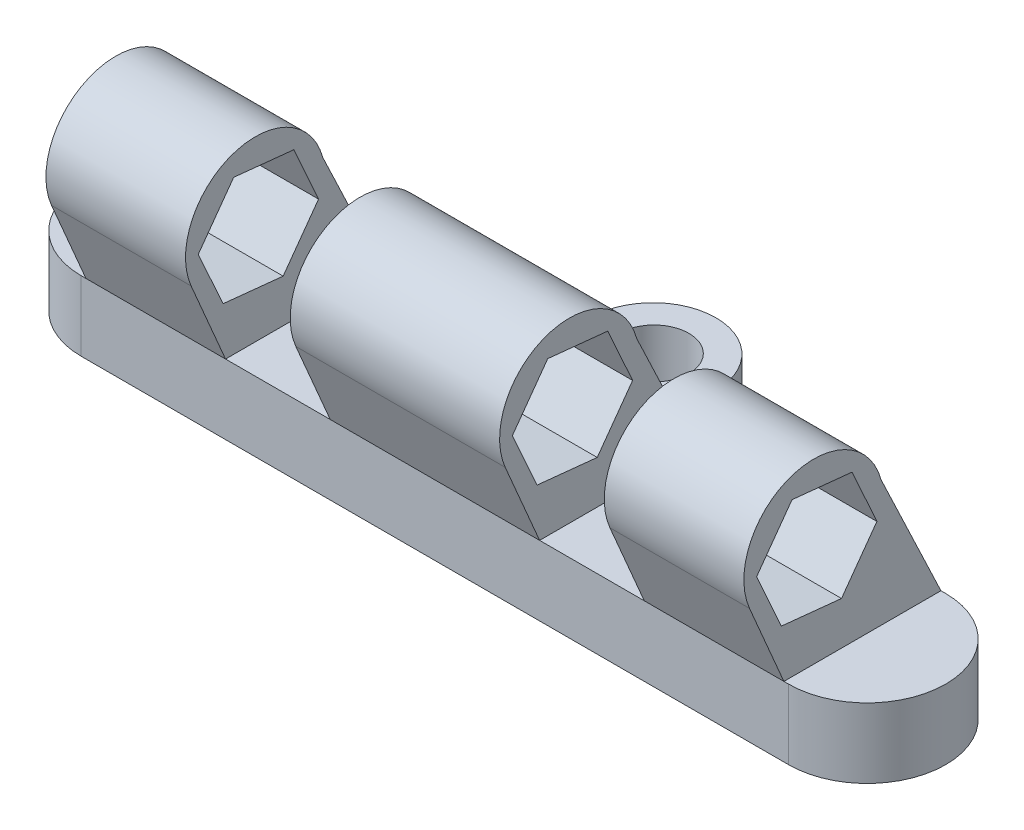
SolidWorks part; units mm, degrees
ref_plane "前视基准面" through (0, 0, 0) normal (0, 0, 1) x (1, 0, 0)
ref_plane "上视基准面" through (0, 0, 0) normal (0, 1, 0) x (1, 0, 0)
ref_plane "右视基准面" through (0, 0, 0) normal (1, 0, 0) x (0, 0, -1)
other "Configuration Table"
sketch "草图2" plane through (0, 0, 0) normal (0, 1, 0) x (1, 0, 0)
  line L1 (-10.1361, 2.25) -> (-1.8018, 2.25)
  line L2 (-10.1361, -2.25) -> (10.1361, -2.25)
  line L4 (-1.8018, 2.25) -> (-1.8018, 4)
  line L5 (1.8018, 2.25) -> (1.8018, 4)
  line L6 (1.8018, 2.25) -> (10.1361, 2.25)
  arc A0 (-10.1361, 2.25) -> (-10.1361, -2.25) centre (-10.1361, 0) ccw
  arc A1 (10.1361, -2.25) -> (10.1361, 2.25) centre (10.1361, 0) ccw
  arc A3 (1.8018, 4) -> (-1.8018, 4) centre (0, 4) ccw
  point P2 (0, 0)
  point P10 (0, 2)
extrude "凸台-拉伸1" add sketch "草图2" along normal blind 2
sketch "草图3" plane through (0, 2, 0) normal (0, 1, 0) x (1, 0, 0)
  circle A0 centre (0, 4.0279) radius 1
extrude "切除-拉伸1" cut sketch "草图3" against normal blind 2
sketch "草图4" plane through (0, 0, 0) normal (1, 0, 0) x (0, 0, -1)
  line L0 (2.25, 2) -> (0.5334, 5.6152)
  line L1 (2.25, 2) -> (-2.25, 2) construction
  line L2 (-2.25, 2) -> (-3.2357, 4.3051)
  line L3 (2.25, 2) -> (-2.25, 2)
  arc A0 (0.5334, 5.6152) -> (-3.2357, 4.3051) centre (-1.3968, 5.0915) ccw
extrude "凸台-拉伸2" add sketch "草图4" along normal mid plane 20
sketch "草图8" plane through (-10, 0, 0) normal (-1, 0, 0) x (0, 0, 1)
  line L0 (0.5994, 3.2326) -> (2.3224, 3.4087)
  line L1 (2.3224, 3.4087) -> (3.0315, 4.989)
  line L2 (3.0315, 4.989) -> (2.0175, 6.3932)
  line L3 (2.0175, 6.3932) -> (0.2944, 6.2171)
  line L4 (0.2944, 6.2171) -> (-0.4146, 4.6368)
  line L5 (-0.4146, 4.6368) -> (0.5994, 3.2326)
  circle A0 centre (1.3084, 4.8129) radius 1.5 construction
  dimension "D1" = 1.5
extrude "切除-拉伸2" cut sketch "草图8" against normal blind 20
sketch "草图9" plane through (0, 0, 0) normal (0, 0, 1) x (1, 0, 0)
  line L0 (0, 0) -> (0, 9.4073) construction
  line L1 (-10.1361, 0) -> (10.1361, 0) construction
  line L2 (10, 2) -> (-10, 2) construction
  line L3 (-6, 2) -> (-3, 2)
  line L4 (-6, 2) -> (-6, 10.4642)
  line L5 (-6, 10.4642) -> (-3, 10.4642)
  line L6 (-3, 2) -> (-3, 10.4642)
  line L7 (6, 10.4642) -> (3, 10.4642)
  line L8 (3, 2) -> (3, 10.4642)
  line L9 (6, 2) -> (3, 2)
  line L10 (6, 2) -> (6, 10.4642)
  dimension "D1" = 3
  dimension "D2" = 3
extrude "切除-拉伸3" cut sketch "草图9" against normal mid plane 20
